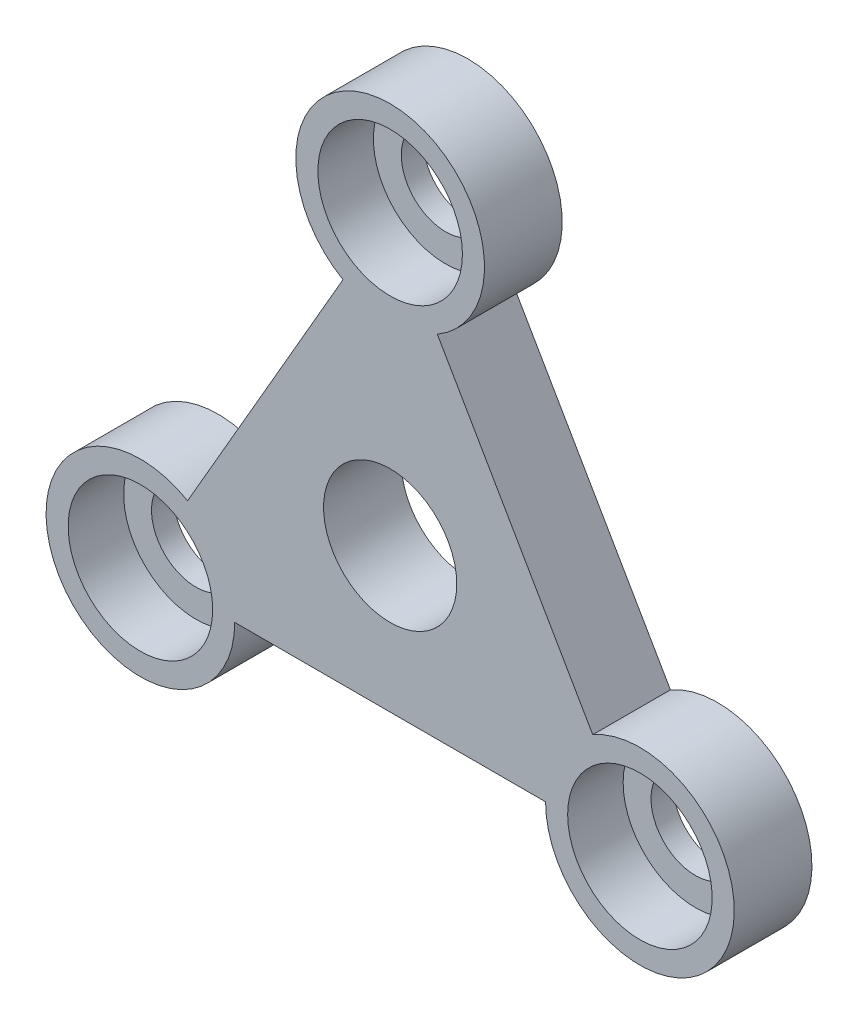
SolidWorks part; units mm, degrees
ref_plane "Front Plane" through (0, 0, 0) normal (0, 0, 1) x (1, 0, 0)
ref_plane "Top Plane" through (0, 0, 0) normal (0, 1, 0) x (1, 0, 0)
ref_plane "Right Plane" through (0, 0, 0) normal (1, 0, 0) x (0, 0, -1)
sketch "Sketch1" plane through (0, 0, 0) normal (0, 0, 1) x (1, 0, 0)
  line L0 (0, 0) -> (45, 0)
  line L1 (45, 0) -> (22.5, 38.9711)
  line L2 (22.5, 38.9711) -> (0, 0)
  dimension "D1" = 60
  dimension "D2" = 60
  dimension "D3" = 45
extrude "Boss-Extrude1" add sketch "Sketch1" along normal blind 7
sketch "Sketch2" plane through (0, 0, 7) normal (0, 0, 1) x (1, 0, 0)
  line L0 (22.5, 0) -> (22.5, 21.3414) construction
  line L1 (0, 0) -> (45, 0) construction
  line L2 (33.75, 19.4856) -> (64.3668, 37.1622) construction
  line L3 (45, 0) -> (22.5, 38.9711) construction
  circle A0 centre (0, 0) radius 8.5
  circle A1 centre (45, 0) radius 8.5
  circle A2 centre (22.5, 38.9711) radius 8.5
  dimension "D1" = 17
extrude "Boss-Extrude2" add sketch "Sketch2" against normal blind 7
sketch "Sketch3" plane through (0, 0, 7) normal (0, 0, 1) x (1, 0, 0)
  line L0 (22.5, 0) -> (22.5, 16.9827) construction
  line L1 (8.5, 0) -> (36.5, 0) construction
  line L2 (33.75, 19.4856) -> (64.939, 37.4925) construction
  line L3 (40.75, 7.3612) -> (26.75, 31.6099) construction
  circle A0 centre (0, 0) radius 6.51
  circle A1 centre (45, 0) radius 6.51
  circle A2 centre (22.5, 38.9711) radius 6.51
  dimension "D1" = 13.02
extrude "Cut-Extrude1" cut sketch "Sketch3" against normal blind 5
sketch "Sketch4" plane through (0, 0, 2) normal (0, 0, 1) x (1, 0, 0)
  line L0 (22.5, 0) -> (22.5, 13.1287) construction
  line L1 (8.5, 0) -> (36.5, 0) construction
  line L2 (33.75, 19.4856) -> (46.9661, 27.1159) construction
  line L3 (40.75, 7.3612) -> (26.75, 31.6099) construction
  circle A0 centre (0, 0) radius 4
  circle A1 centre (45, 0) radius 4
  circle A2 centre (22.5, 38.9711) radius 4
  dimension "D1" = 8
extrude "Cut-Extrude2" cut sketch "Sketch4" against normal through all
sketch "Sketch5" plane through (0, 0, 7) normal (0, 0, 1) x (1, 0, 0)
  line L0 (11.25, 19.4856) -> (23.8884, 12.1888) construction
  line L1 (18.25, 31.6099) -> (4.25, 7.3612) construction
  line L2 (22.5, 0) -> (22.5, 14.2438) construction
  line L3 (8.5, 0) -> (36.5, 0) construction
  circle A0 centre (22.5, 12.9904) radius 6
  dimension "D1" = 12
extrude "Cut-Extrude3" cut sketch "Sketch5" against normal through all
sketch "Sketch6" plane through (0, 0, 7) normal (0, 0, 1) x (1, 0, 0)
  line L0 (0, 0) -> (10.2461, 0) construction
  line L1 (8.5, 0) -> (36.5, 0) construction
  line L2 (0, 0) -> (22.5, 12.9904) construction
